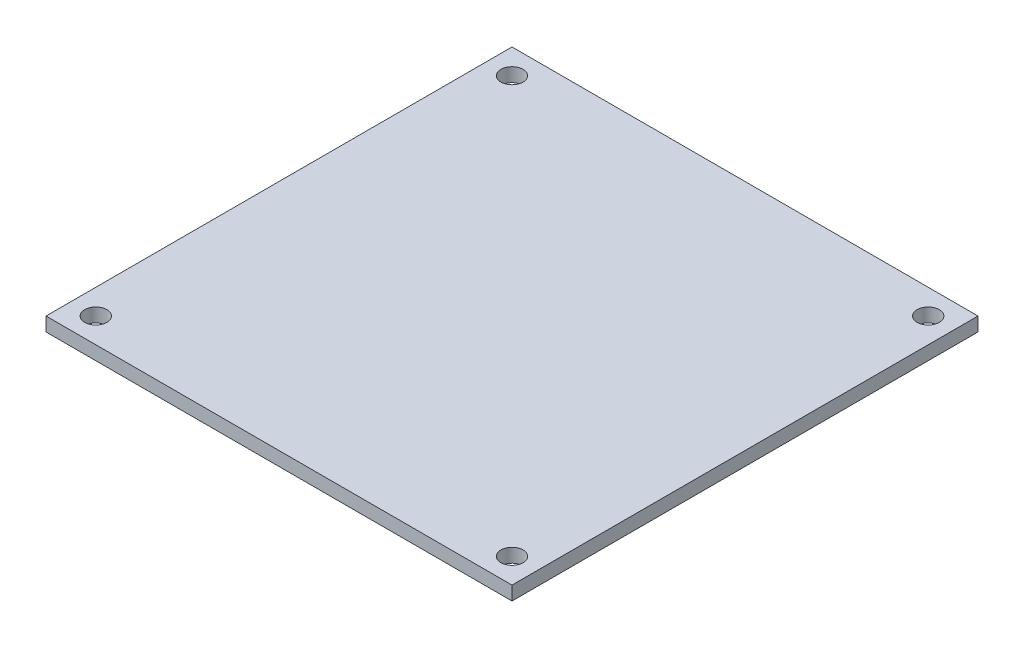
SolidWorks part; units mm, degrees
ref_plane "Front Plane" through (0, 0, 0) normal (0, 0, 1) x (1, 0, 0)
ref_plane "Top Plane" through (0, 0, 0) normal (0, 1, 0) x (1, 0, 0)
ref_plane "Right Plane" through (0, 0, 0) normal (1, 0, 0) x (0, 0, -1)
sketch "Sketch1" plane through (0, 0, 0) normal (0, 1, 0) x (1, 0, 0)
  line L0 (0, 42.0969) -> (0, -42.0969) construction
  line L1 (-42.0969, -42.0969) -> (42.0969, -42.0969)
  line L2 (-42.0969, -42.0969) -> (-42.0969, 42.0969)
  line L3 (-42.0969, 42.0969) -> (42.0969, 42.0969)
  line L4 (42.0969, -42.0969) -> (42.0969, 42.0969)
  line L5 (-42.0969, -42.0969) -> (42.0969, 42.0969) construction
  line L6 (-42.0969, 42.0969) -> (42.0969, -42.0969) construction
  line L7 (-42.0969, 0) -> (42.0969, 0) construction
  circle A0 centre (37.5969, 37.5969) radius 2
  circle A1 centre (-37.5969, 37.5969) radius 2
  circle A2 centre (-37.5969, -37.5969) radius 2
  circle A3 centre (37.5969, -37.5969) radius 2
  point P0 (0, 0)
  point P18 (42.5009, 42.5009)
  dimension "D2" = 4
  dimension "D1" = 4.5
  dimension "D3" = 53.17
extrude "Boss-Extrude1" add sketch "Sketch1" along normal blind 2.5
